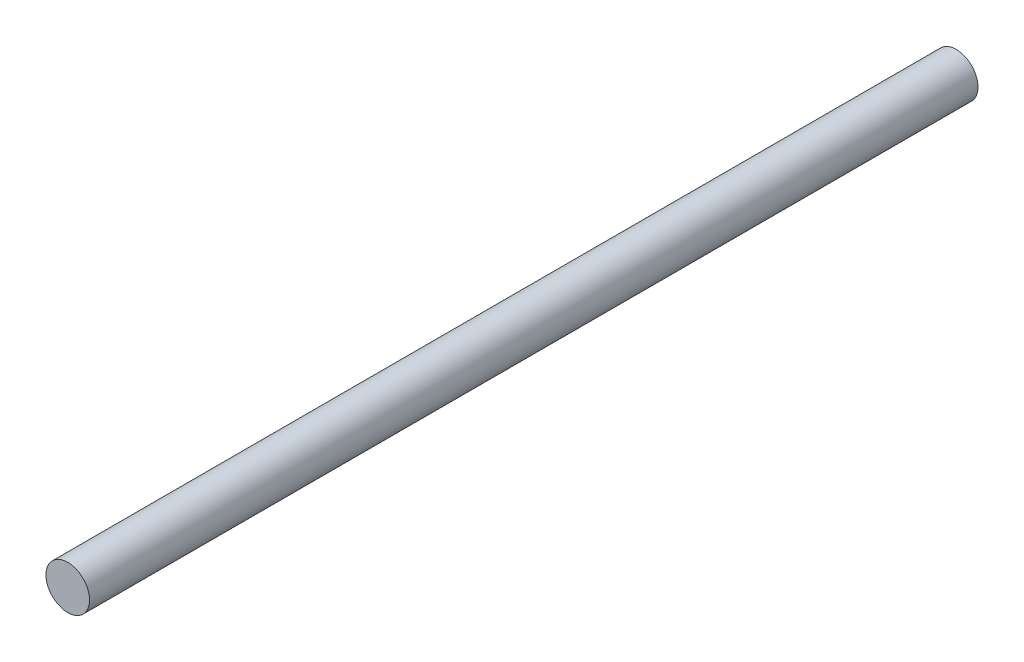
SolidWorks part; units mm, degrees
material "СТ3КП"
ref_plane "Спереди" through (0, 0, 0) normal (0, 0, 1) x (1, 0, 0)
ref_plane "Сверху" through (0, 0, 0) normal (0, 1, 0) x (1, 0, 0)
ref_plane "Справа" through (0, 0, 0) normal (1, 0, 0) x (0, 0, -1)
sketch "Эскиз1" plane through (0, 0, 0) normal (0, 0, 1) x (1, 0, 0)
  circle A0 centre (0, 0) radius 6 construction
  circle A1 centre (0, 0) radius 6
extrude "Бобышка-Вытянуть1" add sketch "Эскиз1" along normal up to surface (122.3 mm away)
mirror "Зеркальное отражение1" about plane through (0, 0, 0) normal (0, 0, 1) of bodies 103
